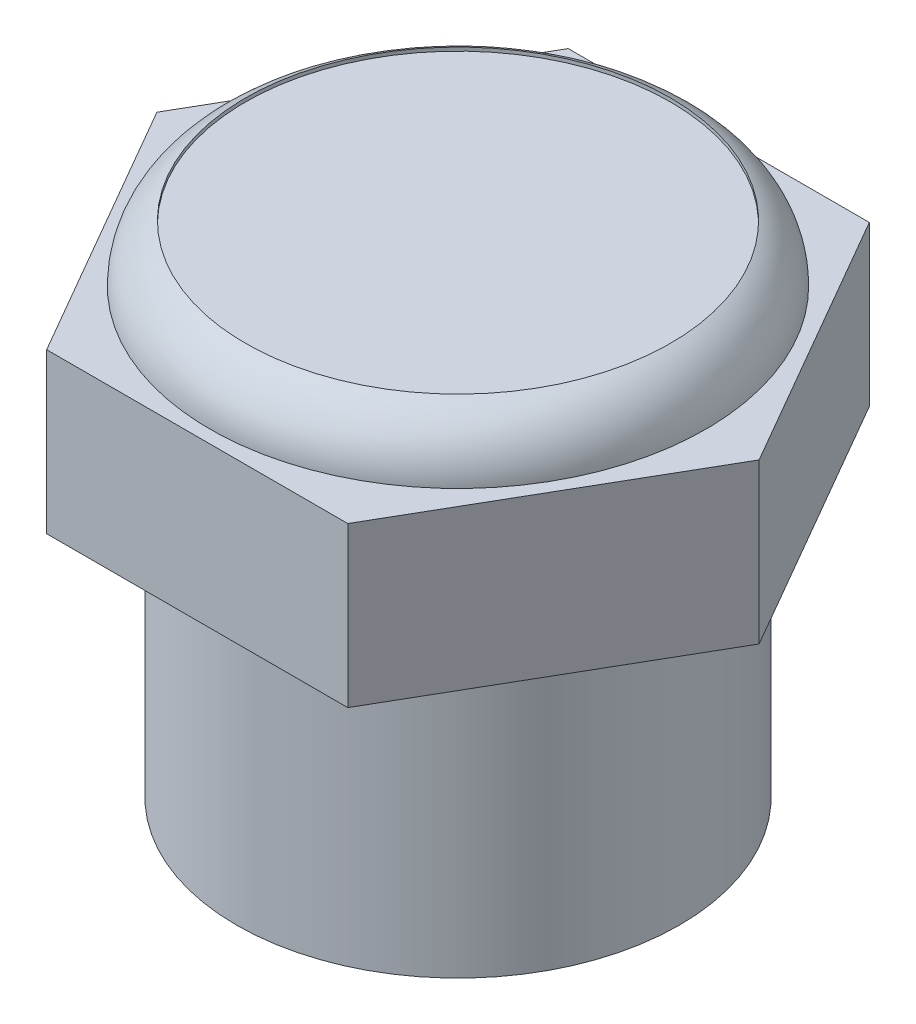
SolidWorks part; units mm, degrees
ref_plane "前视基准面" through (0, 0, 0) normal (0, 0, 1) x (1, 0, 0)
ref_plane "上视基准面" through (0, 0, 0) normal (0, 1, 0) x (1, 0, 0)
ref_plane "右视基准面" through (0, 0, 0) normal (1, 0, 0) x (0, 0, -1)
sketch "草图1" plane through (0, 0, 0) normal (0, 1, 0) x (1, 0, 0)
  circle A0 centre (0, 0) radius 4.5
  circle A1 centre (0, 0) radius 6.25
  dimension "D1" = 12.5
  dimension "D2" = 9
extrude "凸台-拉伸1" add sketch "草图1" along normal blind 8
sketch "草图2" plane through (0, 8, 0) normal (0, 1, 0) x (1, 0, 0)
  line L1 (4.25, 7.3612) -> (-4.25, 7.3612)
  line L2 (-4.25, 7.3612) -> (-8.5, 0)
  line L3 (-8.5, 0) -> (-4.25, -7.3612)
  line L4 (-4.25, -7.3612) -> (4.25, -7.3612)
  line L5 (4.25, -7.3612) -> (8.5, 0)
  line L6 (8.5, 0) -> (4.25, 7.3612)
  circle A0 centre (0, 0) radius 7.3612 construction
  dimension "D1" = 17
extrude "凸台-拉伸2" add sketch "草图2" along normal blind 4.5
sketch "草图3" plane through (0, 0, 0) normal (0, 0, 1) x (1, 0, 0)
  line L0 (6, 14.1) -> (6, 14)
  line L1 (-4.25, 12.5) -> (4.25, 12.5) construction
  line L2 (0, 12.5) -> (7, 12.5)
  line L3 (7, 12.5) -> (7, 9.8394) construction
  line L4 (0, -20.8111) -> (0, 20.8111) construction
  line L7 (6, 14) -> (0, 14)
  line L8 (0, 14) -> (0, 12.5)
  line L9 (4.25, 12.5) -> (8.5, 12.5) construction
  arc A0 (6, 14.1) -> (7, 12.5) centre (5.22, 12.5) cw
  point P13 (0, 0)
  dimension "D2" = 1.5
  dimension "D1" = 1.6
  dimension "D3" = 1
  dimension "D4" = 7
revolve "旋转1" add sketch "草图3" angle 360 about L4
